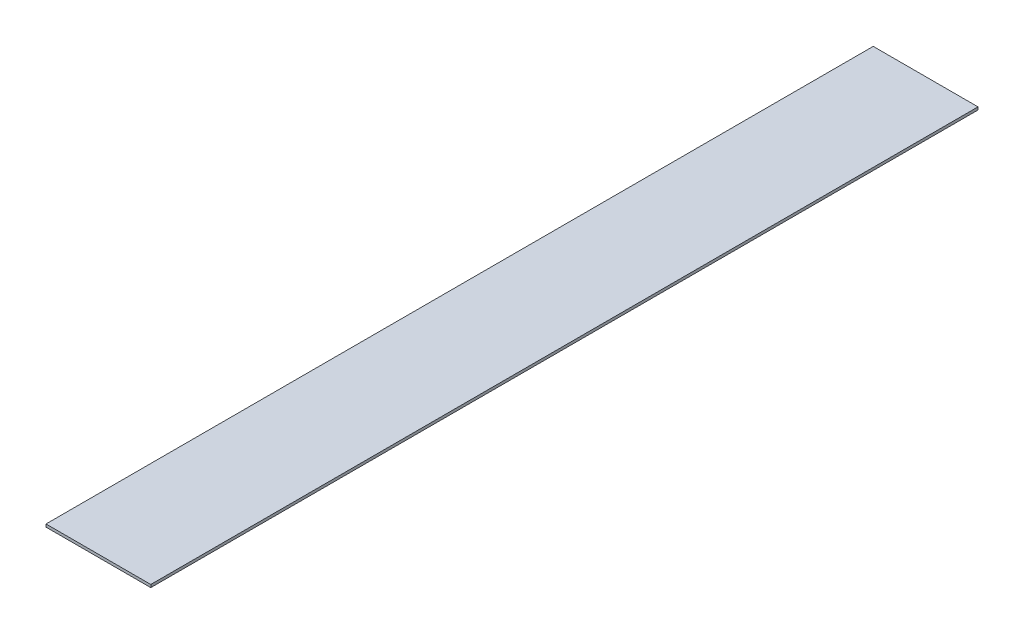
SolidWorks part; units mm, degrees
material "AISI 1010 Aço, barra laminada a quente"
ref_plane "Plano frontal" through (0, 0, 0) normal (0, 0, 1) x (1, 0, 0)
ref_plane "Plano superior" through (0, 0, 0) normal (0, 1, 0) x (1, 0, 0)
ref_plane "Plano direito" through (0, 0, 0) normal (1, 0, 0) x (0, 0, -1)
sketch "Esboço1" plane through (0, 0, 0) normal (0, 0, 1) x (1, 0, 0)
  line L1 (0, 0) -> (19, 0)
  line L2 (0, 0) -> (0, 0.5)
  line L3 (0, 0.5) -> (19, 0.5)
  line L4 (19, 0) -> (19, 0.5)
  dimension "D1" = 19
  dimension "D2" = 0.5
extrude "Ressalto-extrusão1" add sketch "Esboço1" along normal blind 150
